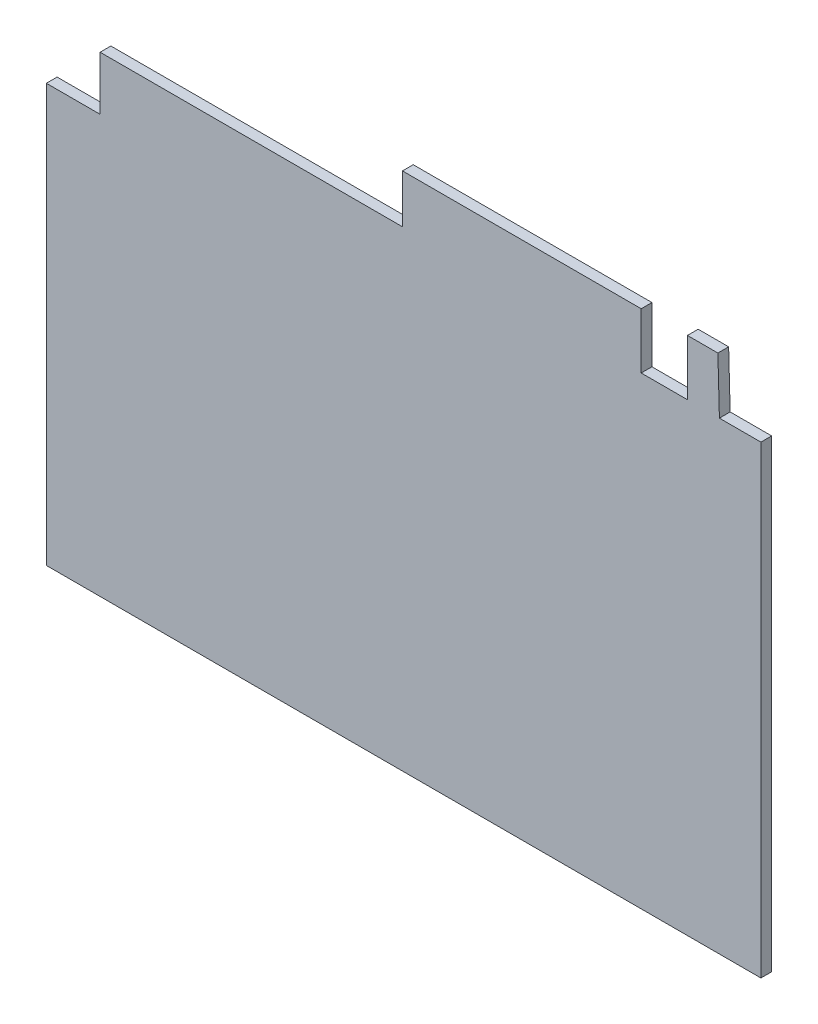
SolidWorks part; units mm, degrees
material "ABS"
ref_plane "Front Plane" through (0, 0, 0) normal (0, 0, 1) x (1, 0, 0)
ref_plane "Top Plane" through (0, 0, 0) normal (0, 1, 0) x (1, 0, 0)
ref_plane "Right Plane" through (0, 0, 0) normal (1, 0, 0) x (0, 0, -1)
sketch "Sketch1" plane through (0, 0, 0) normal (0, 0, 1) x (1, 0, 0)
  line L0 (28.5714, 236.0602) -> (28.5714, 237.0518)
  line L1 (28.5714, 277.1048) -> (28.5714, -22.8952) construction
  line L2 (28.5714, 237.0518) -> (5.4155, 237.0518)
  line L3 (5.4155, 237.0518) -> (4.5714, 268.1048)
  line L4 (4.5714, 268.1048) -> (-12.4286, 268.1048)
  line L5 (-12.4286, 268.1048) -> (-12.4286, 237.0518)
  line L6 (-12.4286, 237.0518) -> (-38.2166, 237.0518)
  line L7 (-38.2166, 237.0518) -> (-38.2166, 268.1048)
  line L8 (-221.4286, 268.1048) -> (28.5714, 268.1048) construction
  line L9 (-38.2166, 268.1048) -> (-171.4286, 268.1048)
  line L10 (-171.4286, 268.1048) -> (-171.4286, 241.1048)
  line L11 (-171.4286, 241.1048) -> (-370.1235, 241.1048)
  line L12 (-370.1235, 241.1048) -> (-370.1235, -22.8952)
  line L13 (-370.1235, -22.8952) -> (28.5714, -22.8952)
  line L14 (28.5714, -22.8952) -> (28.5714, 236.0602)
extrude "Boss-Extrude1" add sketch "Sketch1" along normal blind 6
sketch "Sketch2" plane through (0, 0, 6) normal (0, 0, 1) x (1, 0, 0)
  line L1 (-370.1235, 241.1048) -> (-340.1235, 241.1048)
  line L2 (-370.1235, 241.1048) -> (-370.1235, 211.1048)
  line L3 (-370.1235, 211.1048) -> (-340.1235, 211.1048)
  line L4 (-340.1235, 241.1048) -> (-340.1235, 211.1048)
  dimension "D1" = 30
  dimension "D2" = 30
extrude "Cut-Extrude1" cut sketch "Sketch2" against normal blind 10
sketch "Sketch3" plane through (0, 0, 6) normal (0, 0, 1) x (1, 0, 0)
  line L0 (28.5714, -22.8952) -> (28.5714, 237.0518) construction
  line L1 (-370.1235, -22.8952) -> (28.5714, -22.8952)
  line L2 (-370.1235, -22.8952) -> (-370.1235, -21.8952)
  line L3 (-370.1235, -21.8952) -> (28.5714, -21.8952)
  line L4 (28.5714, -22.8952) -> (28.5714, -21.8952)
  dimension "D1" = 1
extrude "Cut-Extrude2" cut sketch "Sketch3" against normal blind 10
